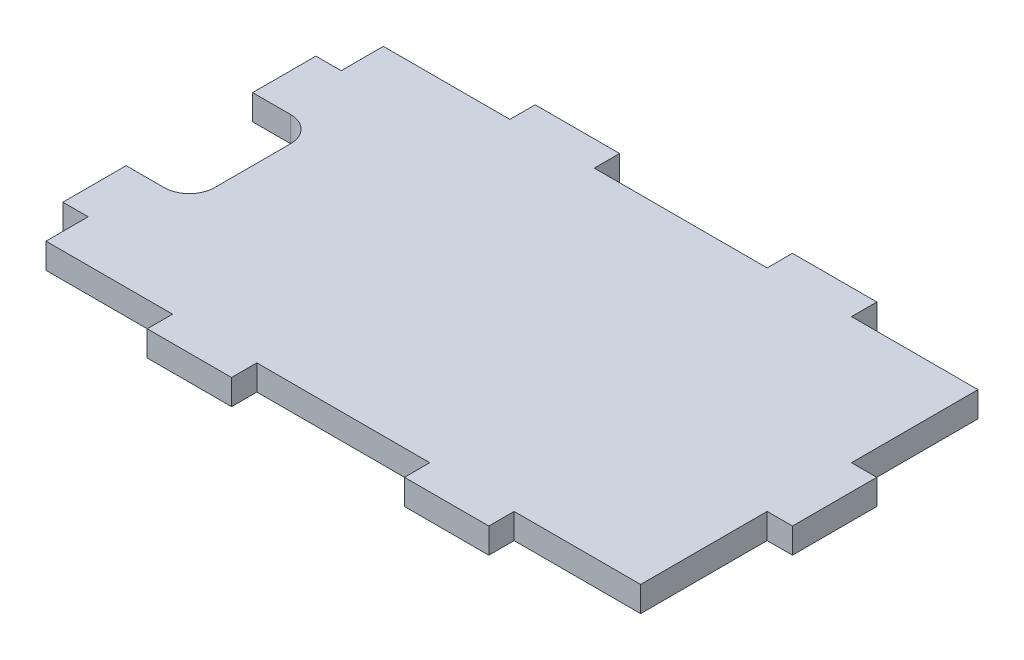
SolidWorks part; units mm, degrees
ref_plane "Front Plane" through (0, 0, 0) normal (0, 0, 1) x (1, 0, 0)
ref_plane "Top Plane" through (0, 0, 0) normal (0, 1, 0) x (1, 0, 0)
ref_plane "Right Plane" through (0, 0, 0) normal (1, 0, 0) x (0, 0, -1)
sketch "Sketch1" plane through (0, 0, 0) normal (0, 1, 0) x (1, 0, 0)
  line L1 (0, 0) -> (141, 0)
  line L2 (0, 0) -> (0, -80)
  line L3 (0, -80) -> (141, -80)
  line L4 (141, 0) -> (141, -80)
  dimension "D1" = 80
  dimension "D2" = 141
extrude "Boss-Extrude1" add sketch "Sketch1" along normal blind 6
sketch "Sketch2" plane through (0, 0, 80) normal (0, 0, 1) x (1, 0, 0)
  line L0 (0, 0) -> (141, 0) construction
  line L1 (30, 0) -> (50, 0)
  line L2 (30, 0) -> (30, 6)
  line L3 (30, 6) -> (50, 6)
  line L4 (50, 0) -> (50, 6)
  line L5 (0, 6) -> (141, 6) construction
  line L6 (0, 6) -> (0, 0) construction
  line L7 (91, 0) -> (111, 0)
  line L8 (91, 0) -> (91, 6)
  line L9 (91, 6) -> (111, 6)
  line L10 (111, 0) -> (111, 6)
  line L11 (141, 6) -> (141, 0) construction
  dimension "D1" = 20
  dimension "D2" = 20
  dimension "D3" = 30
  dimension "D4" = 30
extrude "Boss-Extrude2" add sketch "Sketch2" along normal blind 6
sketch "Sketch3" plane through (0, 0, 0) normal (0, 0, -1) x (-1, 0, 0)
  line L12 (-91, 6) -> (-91, 0) construction
  line L13 (-91, 0) -> (-111, 0) construction
  line L14 (-111, 0) -> (-111, 6) construction
  line L15 (-111, 6) -> (-91, 6) construction
  line L16 (-30, 6) -> (-30, 0) construction
  line L17 (-30, 0) -> (-50, 0) construction
  line L18 (-50, 0) -> (-50, 6) construction
  line L19 (-50, 6) -> (-30, 6) construction
  line L20 (-91, 6) -> (-91, 0)
  line L21 (-91, 0) -> (-111, 0)
  line L22 (-111, 0) -> (-111, 6)
  line L23 (-111, 6) -> (-91, 6)
  line L24 (-30, 6) -> (-30, 0)
  line L25 (-30, 0) -> (-50, 0)
  line L26 (-50, 0) -> (-50, 6)
  line L27 (-50, 6) -> (-30, 6)
extrude "Boss-Extrude3" add sketch "Sketch3" along normal blind 6
sketch "Sketch4" plane through (0, 0, 0) normal (-1, 0, 0) x (0, 0, 1)
  line L0 (0, 0) -> (80, 0) construction
  line L1 (10, 0) -> (25, 0)
  line L2 (10, 0) -> (10, 6)
  line L3 (10, 6) -> (25, 6)
  line L4 (25, 0) -> (25, 6)
  line L5 (0, 6) -> (80, 6) construction
  line L6 (80, 6) -> (80, 0) construction
  line L7 (55, 0) -> (70, 0)
  line L8 (55, 0) -> (55, 6)
  line L9 (55, 6) -> (70, 6)
  line L10 (70, 0) -> (70, 6)
  dimension "D1" = 15
  dimension "D2" = 15
  dimension "D3" = 10
  dimension "D4" = 10
extrude "Boss-Extrude4" add sketch "Sketch4" along normal blind 6
sketch "Sketch5" plane through (141, 0, 0) normal (1, 0, 0) x (0, 0, -1)
  line L0 (-80, 6) -> (0, 6) construction
  line L1 (-80, 6) -> (-80, 0) construction
  line L5 (-80, 0) -> (0, 0) construction
  line L7 (-50, 6) -> (-30, 6)
  line L8 (-50, 6) -> (-50, 0)
  line L9 (-50, 0) -> (-30, 0)
  line L10 (-30, 6) -> (-30, 0)
  dimension "D1" = 30
  dimension "D2" = 20
extrude "Boss-Extrude5" add sketch "Sketch5" along normal blind 6
sketch "Sketch6" plane through (0, 6, 0) normal (0, 1, 0) x (1, 0, 0)
  line L0 (0, -25) -> (0, -55) construction
  line L1 (0, -25) -> (3, -25)
  line L2 (0, -25) -> (0, -55)
  line L3 (0, -55) -> (3, -55)
  line L4 (9, -31) -> (9, -49)
  line L5 (0, 0) -> (0, -10) construction
  line L6 (-6, -55) -> (0, -55) construction
  line L7 (-6, -25) -> (0, -25) construction
  arc A0 (3, -55) -> (9, -49) centre (3, -49) ccw
  arc A1 (3, -25) -> (9, -31) centre (3, -31) cw
  dimension "D2" = 6
  dimension "D1" = 9
extrude "Cut-Extrude1" cut sketch "Sketch6" against normal blind 6
